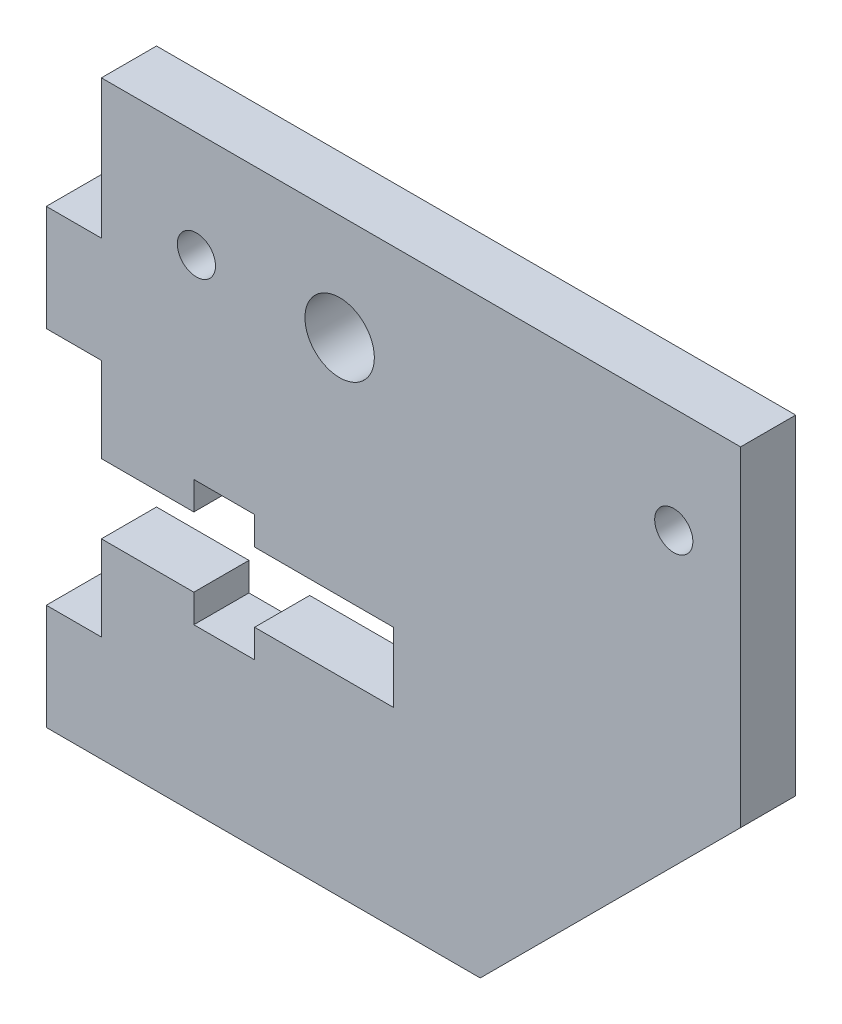
SolidWorks part; units mm, degrees
ref_plane "Front Plane" through (0, 0, 0) normal (0, 0, 1) x (1, 0, 0)
ref_plane "Top Plane" through (0, 0, 0) normal (0, 1, 0) x (1, 0, 0)
ref_plane "Right Plane" through (0, 0, 0) normal (1, 0, 0) x (0, 0, -1)
sketch "Sketch1" plane through (0, 0, 0) normal (0, 0, 1) x (1, 0, 0)
  line L0 (10.8, 34) -> (10.8, 21.8)
  line L1 (0, 0) -> (40, 0)
  line L2 (0, 0) -> (0, 6.1)
  line L3 (3.175, 34) -> (10.8, 34)
  line L4 (40, 0) -> (40, 34)
  line L5 (10.8, 21.8) -> (34, 21.8)
  line L6 (34, 21.8) -> (34, 34)
  line L7 (34, 34) -> (40, 34)
  line L8 (-11.825, 17) -> (40, 17) construction
  line L9 (0, 19.9) -> (3.175, 19.9)
  line L10 (12, 15) -> (20, 15)
  line L11 (0, 6.1) -> (3.175, 6.1)
  line L12 (3.175, 19.9) -> (3.175, 15)
  line L13 (3.175, 15) -> (8.5, 15)
  line L14 (8.5, 11) -> (8.5, 9.375)
  line L15 (3.175, 11) -> (8.5, 11)
  line L16 (20, 15) -> (20, 11)
  line L17 (8.5, 16.625) -> (12, 16.625)
  line L18 (8.5, 16.625) -> (8.5, 15)
  line L19 (8.5, 9.375) -> (12, 9.375)
  line L20 (12, 16.625) -> (12, 15)
  line L21 (3.175, 11) -> (3.175, 6.1)
  line L22 (12, 11) -> (12, 9.375)
  line L23 (0, 19.9) -> (0, 26)
  line L24 (12, 11) -> (20, 11)
  line L25 (10.8, 34) -> (34, 34)
  line L26 (0, 26) -> (3.175, 26)
  line L27 (0, 26) -> (0, 34)
  line L28 (0, 34) -> (3.175, 34)
  line L29 (3.175, 26) -> (3.175, 34)
  circle A0 centre (8.65, 27.9) radius 1.1
  circle A1 centre (36.15, 27.9) radius 1.1
  circle A2 centre (16.9, 27.9) radius 2
  dimension "D8" = 2.2
  dimension "D9" = 2.2
  dimension "D24" = 4
  dimension "D1" = 34
  dimension "D2" = 40
  dimension "D3" = 12.2
  dimension "D4" = 23.2
  dimension "D5" = 6
  dimension "D6" = 27.5
  dimension "D7" = 6.1
  dimension "D10" = 2.15
  dimension "D11" = 19.9
  dimension "D12" = 6.1
  dimension "D13" = 3.175
  dimension "D14" = 4
  dimension "D15" = 7.25
  dimension "D16" = 15
  dimension "D17" = 16.625
  dimension "D18" = 3.5
  dimension "D19" = 20
  dimension "D20" = 8.5
  dimension "D21" = 6.1
  dimension "D22" = 3.175
  dimension "D23" = 16.9
extrude "Boss-Extrude1" add sketch "Sketch1" along normal blind 3.175 contours L12 L8 L4 L7 L6 L5 L0 L3 L29 L26 L23 L9 A0 A1 | L8 L12 L13 L18 L17 L20 L10 L16 L24 L22 L19 L14 L15 L21 L11 L2 L1 L4 | L25 L0 L5 L6 A2
chamfer "Chamfer1" distance 15 angle 45 1 edges at (40, 0, 1.5875)
